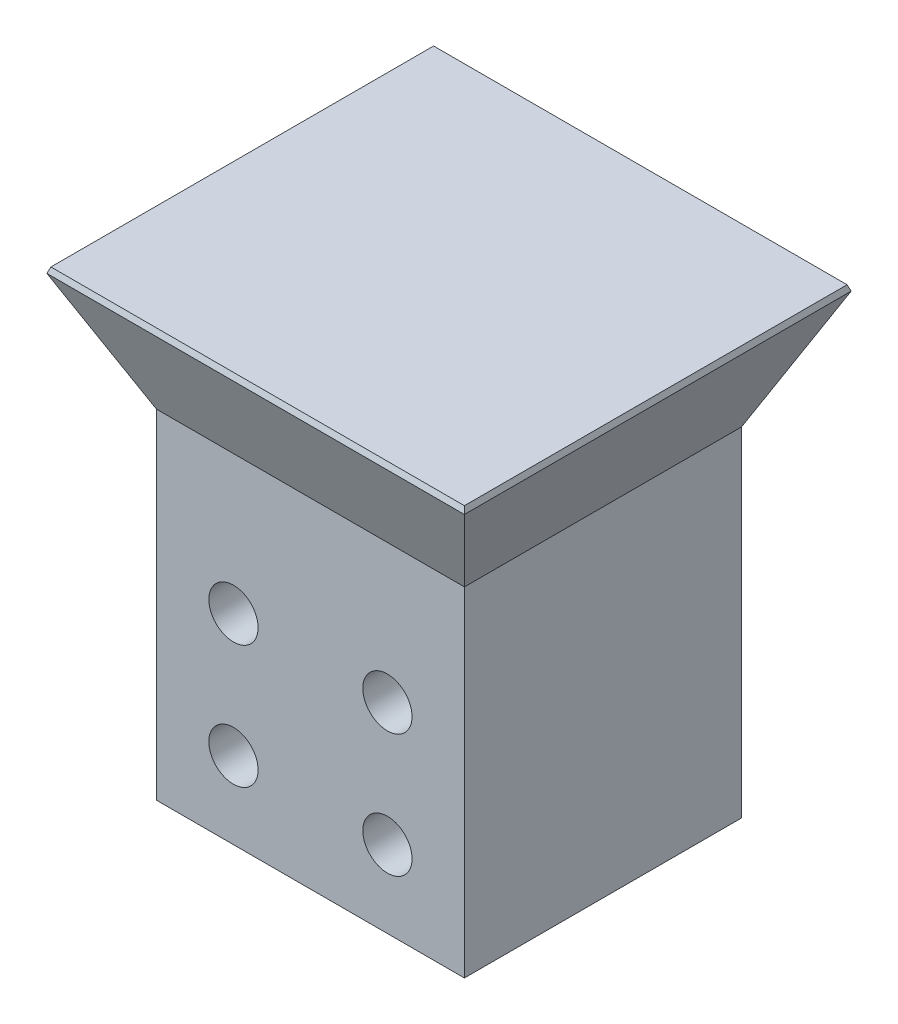
SolidWorks part; units mm, degrees
material "PLA+"
ref_plane "Front Plane" through (0, 0, 0) normal (0, 0, 1) x (1, 0, 0)
ref_plane "Top Plane" through (0, 0, 0) normal (0, 1, 0) x (1, 0, 0)
ref_plane "Right Plane" through (0, 0, 0) normal (1, 0, 0) x (0, 0, -1)
sketch "Sketch1" plane through (0, 0, 0) normal (0, 1, 0) x (1, 0, 0)
  line L1 (-10, -9) -> (10, -9)
  line L2 (-10, -9) -> (-10, 9)
  line L3 (-10, 9) -> (10, 9)
  line L4 (10, -9) -> (10, 9)
  line L5 (-10, -9) -> (10, 9) construction
  line L6 (-10, 9) -> (10, -9) construction
  point P0 (0, 0)
  dimension "D1" = 18
  dimension "D2" = 20
extrude "Boss-Extrude1" add sketch "Sketch1" along normal blind 22
sketch "Sketch2" plane through (0, 22, 0) normal (0, 1, 0) x (1, 0, 0)
  line L4 (10, -9) -> (10, 9)
  line L5 (10, 9) -> (-10, 9)
  line L6 (-10, 9) -> (-10, -9)
  line L7 (-10, -9) -> (10, -9)
  line L8 (10, -9) -> (10, 9)
  line L9 (10, 9) -> (-10, 9)
  line L10 (-10, 9) -> (-10, -9)
  line L11 (-10, -9) -> (10, -9)
  dimension "D1" = 0
extrude "Boss-Extrude2" add sketch "Sketch2" along normal blind 8 draft 25 draft outward yes
sketch "Sketch3" plane through (0, 0, 9) normal (0, 0, 1) x (1, 0, 0)
  line L0 (-10, 0) -> (10, 0) construction
  line L1 (-10, 22) -> (-10, 0) construction
  circle A0 centre (-5, 13) radius 1.6
  circle A1 centre (5, 13) radius 1.6
  circle A2 centre (-5, 5) radius 1.6
  circle A3 centre (5, 5) radius 1.6
  dimension "D1" = 3.2
  dimension "D2" = 3.2
  dimension "D3" = 3.2
  dimension "D4" = 3.2
  dimension "D5" = 5
  dimension "D6" = 8
  dimension "D7" = 5
  dimension "D8" = 10
extrude "Cut-Extrude1" cut sketch "Sketch3" against normal through all
chamfer "Chamfer1" distance 0.4 angle 45 4 edges at (-13.7305, 30, 0) (0, 30, -12.7305) (13.7305, 30, 0) (0, 30, 12.7305)
